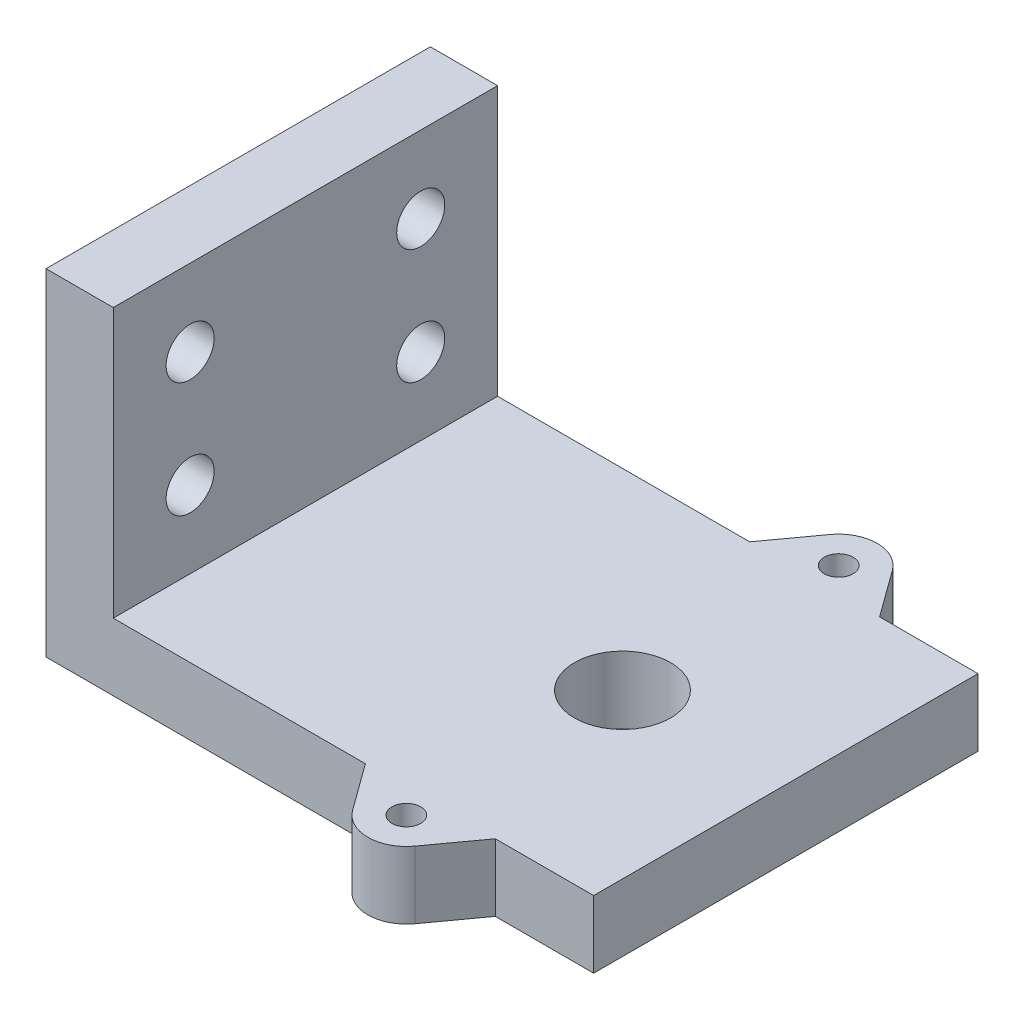
SolidWorks part; units mm, degrees
ref_plane "Front Plane" through (0, 0, 0) normal (0, 0, 1) x (1, 0, 0)
ref_plane "Top Plane" through (0, 0, 0) normal (0, 1, 0) x (1, 0, 0)
ref_plane "Right Plane" through (0, 0, 0) normal (1, 0, 0) x (0, 0, -1)
sketch "Sketch1" plane through (0, 0, 0) normal (0, 0, 1) x (1, 0, 0)
  line L0 (0, 0) -> (0, 35)
  line L1 (0, 35) -> (7, 35)
  line L2 (7, 35) -> (7, 7)
  line L3 (7, 7) -> (57, 7)
  line L4 (57, 7) -> (57, 0)
  line L5 (57, 0) -> (0, 0)
  dimension "D1" = 35
  dimension "D2" = 7
  dimension "D3" = 50
extrude "Boss-Extrude1" add sketch "Sketch1" along normal mid plane 40
sketch "Sketch2" plane through (0, 7, 0) normal (0, 1, 0) x (1, 0, 0)
  circle A0 centre (40, 0) radius 5
  dimension "D1" = 10
  dimension "D2" = 40
extrude "Cut-Extrude1" cut sketch "Sketch2" against normal through all
sketch "Sketch3" plane through (7, 0, 0) normal (1, 0, 0) x (0, 0, -1)
  line L0 (-20, 35) -> (20, 35) construction
  line L1 (20, 7) -> (20, 35) construction
  line L2 (-20, 7) -> (20, 7) construction
  line L3 (-20, 7) -> (-20, 35) construction
  circle A0 centre (12, 27) radius 2.5
  circle A1 centre (12, 15) radius 2.5
  circle A2 centre (-12, 27) radius 2.5
  circle A3 centre (-12, 15) radius 2.5
  dimension "D5" = 5
  dimension "D1" = 8
  dimension "D2" = 8
  dimension "D3" = 8
  dimension "D4" = 8
extrude "Cut-Extrude2" cut sketch "Sketch3" against normal through all
sketch "Sketch4" plane through (0, 7, 0) normal (0, 1, 0) x (1, 0, 0)
  line L0 (40, 22.5) -> (40, -22.5) construction
  line L2 (36.765, 24.8526) -> (33.2361, 20)
  line L3 (57, 20) -> (7, 20) construction
  line L4 (43.235, 24.8526) -> (46.7639, 20)
  line L5 (43.235, -24.8526) -> (46.7639, -20)
  line L6 (57, -20) -> (7, -20) construction
  line L7 (36.765, -24.8526) -> (33.2361, -20)
  line L8 (33.2361, -20) -> (46.7639, -20)
  line L9 (33.2361, 20) -> (46.7639, 20)
  circle A0 centre (40, 0) radius 5 construction
  circle A1 centre (40, 22.5) radius 1.5
  circle A2 centre (40, -22.5) radius 1.5
  arc A3 (36.765, 24.8526) -> (43.235, 24.8526) centre (40, 22.5) cw
  arc A4 (36.765, -24.8526) -> (43.235, -24.8526) centre (40, -22.5) ccw
  point P4 (40, 0)
  dimension "D2" = 3
  dimension "D3" = 4
  dimension "D1" = 45
  dimension "D4" = 6
extrude "Boss-Extrude2" add sketch "Sketch4" against normal up to surface (7 mm away) up to face at (40, 0, 5)
